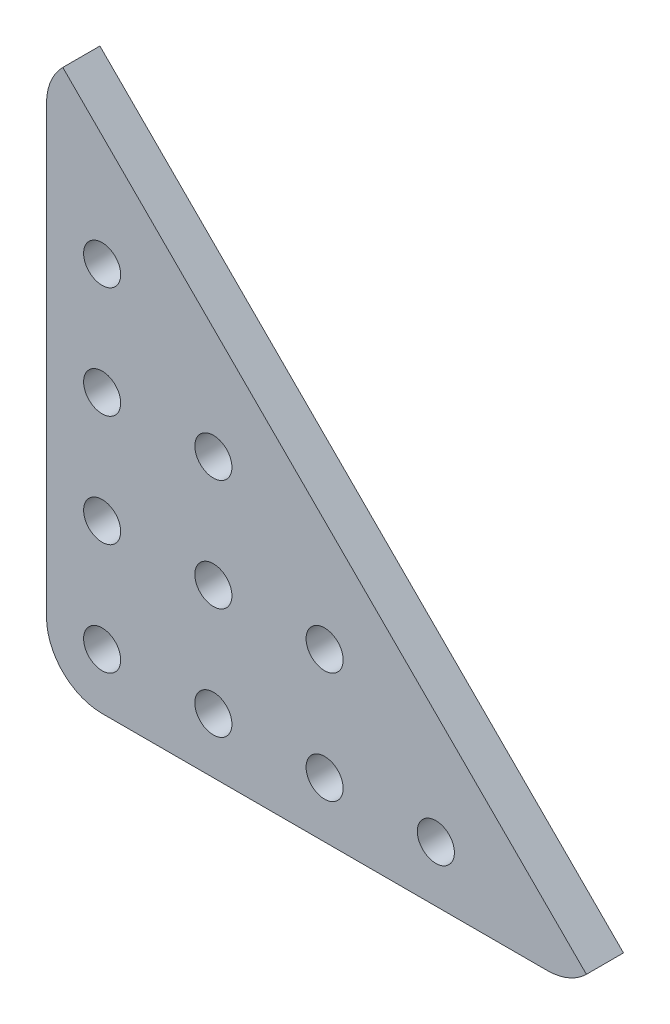
SolidWorks part; units mm, degrees
ref_plane "Alzado" through (0, 0, 0) normal (0, 0, 1) x (1, 0, 0)
ref_plane "Planta" through (0, 0, 0) normal (0, 1, 0) x (1, 0, 0)
ref_plane "Vista lateral" through (0, 0, 0) normal (1, 0, 0) x (0, 0, -1)
sketch "Model" plane through (0, 0, 0) normal (0, 0, 1) x (1, 0, 0)
  line L0 (-105.9434, 101.0565) -> (-105.9434, 65.0565)
  line L1 (-101.4434, 60.5565) -> (-65.4434, 60.5565)
  line L2 (-104.6254, 104.2385) -> (-62.2614, 61.8746)
  circle A0 centre (-101.4434, 92.0565) radius 1.5
  circle A1 centre (-101.4434, 83.0565) radius 1.5
  circle A2 centre (-92.4434, 83.0565) radius 1.5
  arc A3 (-104.6254, 104.2385) -> (-105.9434, 101.0565) centre (-101.4434, 101.0565) ccw
  arc A4 (-105.9434, 65.0565) -> (-101.4434, 60.5565) centre (-101.4434, 65.0565) ccw
  arc A5 (-65.4434, 60.5565) -> (-62.2614, 61.8746) centre (-65.4434, 65.0565) ccw
  circle A6 centre (-101.4434, 74.0565) radius 1.5
  circle A7 centre (-92.4434, 74.0565) radius 1.5
  circle A8 centre (-83.4434, 74.0565) radius 1.5
  circle A9 centre (-101.4434, 65.0565) radius 1.5
  circle A10 centre (-92.4434, 65.0565) radius 1.5
  circle A11 centre (-83.4434, 65.0565) radius 1.5
  circle A12 centre (-74.4434, 65.0565) radius 1.5
extrude "Saliente-Extruir1" add sketch "Model" along normal blind 3
